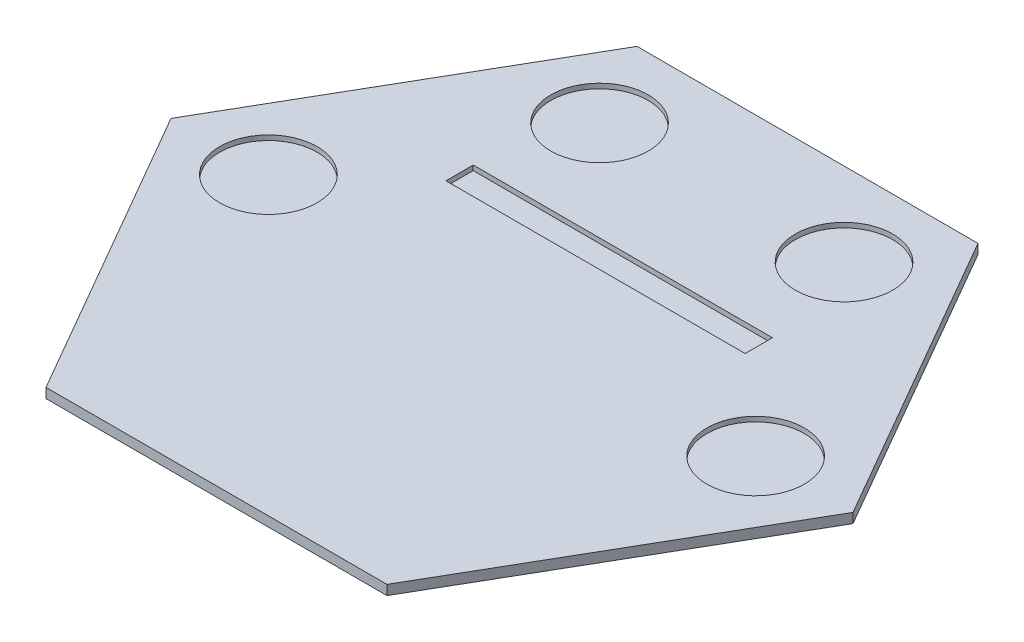
SolidWorks part; units mm, degrees
ref_plane "Front Plane" through (0, 0, 0) normal (0, 0, 1) x (1, 0, 0)
ref_plane "Top Plane" through (0, 0, 0) normal (0, 1, 0) x (1, 0, 0)
ref_plane "Right Plane" through (0, 0, 0) normal (1, 0, 0) x (0, 0, -1)
sketch "Sketch1" plane through (0, 0, 0) normal (0, 1, 0) x (1, 0, 0)
  line L19 (175.1018, 303.0501) -> (-174.8982, 303.1676)
  line L20 (-174.8982, 303.1676) -> (-350, 0.1175)
  line L21 (-350, 0.1175) -> (-175.1018, -303.0501)
  line L22 (-175.1018, -303.0501) -> (174.8982, -303.1676)
  line L23 (174.8982, -303.1676) -> (350, -0.1175)
  line L24 (350, -0.1175) -> (175.1018, 303.0501)
  circle A4 centre (0, 0) radius 350 construction
  dimension "D1" = 700
extrude "Boss-Extrude1" add sketch "Sketch1" along normal blind 10
sketch "Sketch2" plane through (0, 10, 0) normal (0, 1, 0) x (1, 0, 0)
  line L1 (-150, -15) -> (150, -15)
  line L2 (-150, -15) -> (-150, 15)
  line L3 (-150, 15) -> (150, 15)
  line L4 (150, -15) -> (150, 15)
  line L5 (-150, -15) -> (150, 15) construction
  line L6 (-150, 15) -> (150, -15) construction
  circle A0 centre (-250, 0.0412) radius 50
  circle A1 centre (-126.0766, 215.8954) radius 50
  circle A2 centre (250, 0) radius 50
  circle A3 centre (122.9968, 217.6975) radius 50
  point P11 (0, 0)
  dimension "D1" = 100
  dimension "D2" = 100
  dimension "D3" = 100
  dimension "D4" = 100
  dimension "D5" = 300
  dimension "D6" = 30
extrude "Cut-Extrude2" cut sketch "Sketch2" along direction (0, 1, 0) on the side against the normal blind 5 contours A0 | A1 | A3 | A2
sketch "Sketch3" plane through (0, 10, 0) normal (0, 1, 0) x (1, 0, 0)
  line L1 (-153.5, 85.7175) -> (153.5, 85.7175)
  line L2 (-153.5, 85.7175) -> (-153.5, 113.7175)
  line L3 (-153.5, 113.7175) -> (153.5, 113.7175)
  line L4 (153.5, 85.7175) -> (153.5, 113.7175)
  line L5 (-153.5, 85.7175) -> (153.5, 113.7175) construction
  line L6 (-153.5, 113.7175) -> (153.5, 85.7175) construction
  point P0 (0, 0)
  dimension "D1" = 307
  dimension "D2" = 28
extrude "Cut-Extrude3" cut sketch "Sketch3" against normal blind 5
sketch "Sketch4" plane through (0, 10, 0) normal (0, 1, 0) x (1, 0, 0)
  line L0 (-290.5047, -103.0114) -> (290.4354, -103.2064) construction
  line L1 (55.3728, -17.9295) -> (-55.442, -17.9295)
  line L2 (55.3728, -17.9295) -> (55.3728, -188.2883)
  line L3 (55.3728, -188.2883) -> (-55.442, -188.2883)
  line L4 (-55.442, -17.9295) -> (-55.442, -188.2883)
  line L5 (55.3728, -17.9295) -> (-55.442, -188.2883) construction
  line L6 (55.3728, -188.2883) -> (-55.442, -17.9295) construction
  point P0 (-0.0346, -103.1089)
